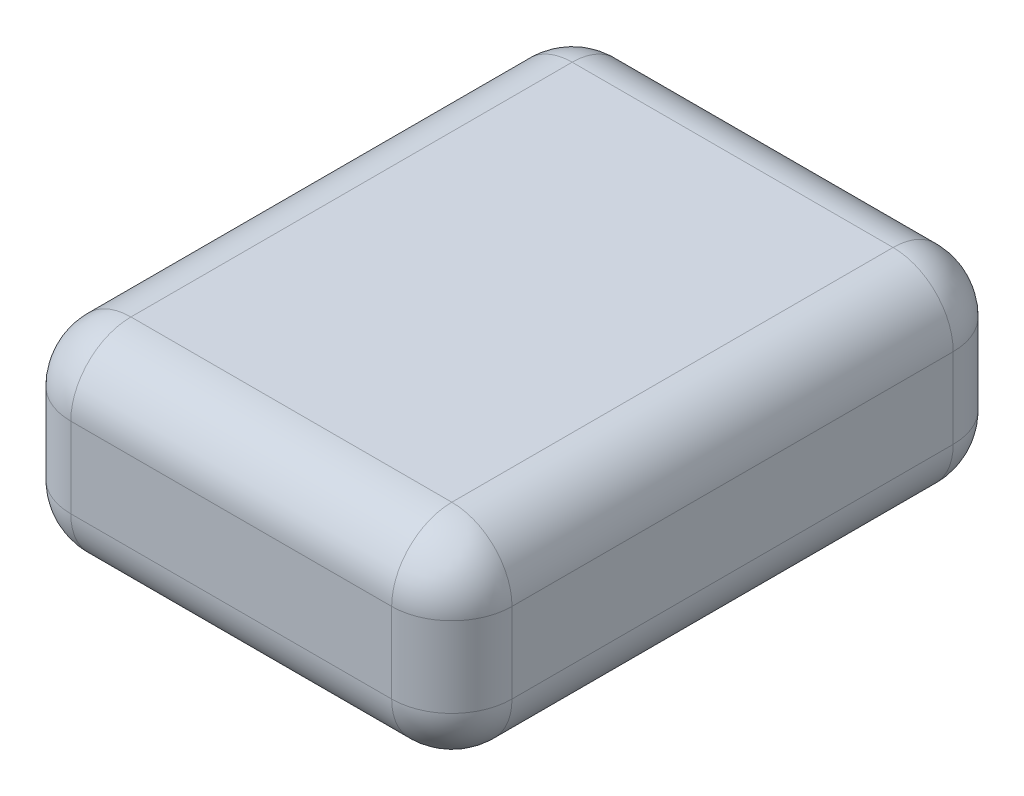
SolidWorks part; units mm, degrees
ref_plane "前视基准面" through (0, 0, 0) normal (0, 0, 1) x (1, 0, 0)
ref_plane "上视基准面" through (0, 0, 0) normal (0, 1, 0) x (1, 0, 0)
ref_plane "右视基准面" through (0, 0, 0) normal (1, 0, 0) x (0, 0, -1)
other "Configuration Table"
sketch "草图1" plane through (0, 0, 0) normal (0, 1, 0) x (1, 0, 0)
  line L1 (-11, 14) -> (11, 14)
  line L2 (-11, 14) -> (-11, -14)
  line L3 (-11, -14) -> (11, -14)
  line L4 (11, 14) -> (11, -14)
  line L5 (-11, 14) -> (11, -14) construction
  line L6 (-11, -14) -> (11, 14) construction
  point P0 (0, 0)
  dimension "D1" = 28
  dimension "D2" = 22
extrude "凸台-拉伸1" add sketch "草图1" along normal blind 10
fillet "圆角1" radius 3 12 edges at (0, 0, 14) (-11, 5, 14) (11, 5, 14) (11, 0, 0) (11, 5, -14) (0, 0, -14) (-11, 5, -14) (-11, 0, 0) (0, 10, -14) (-11, 10, 0) (0, 10, 14) (11, 10, 0)
